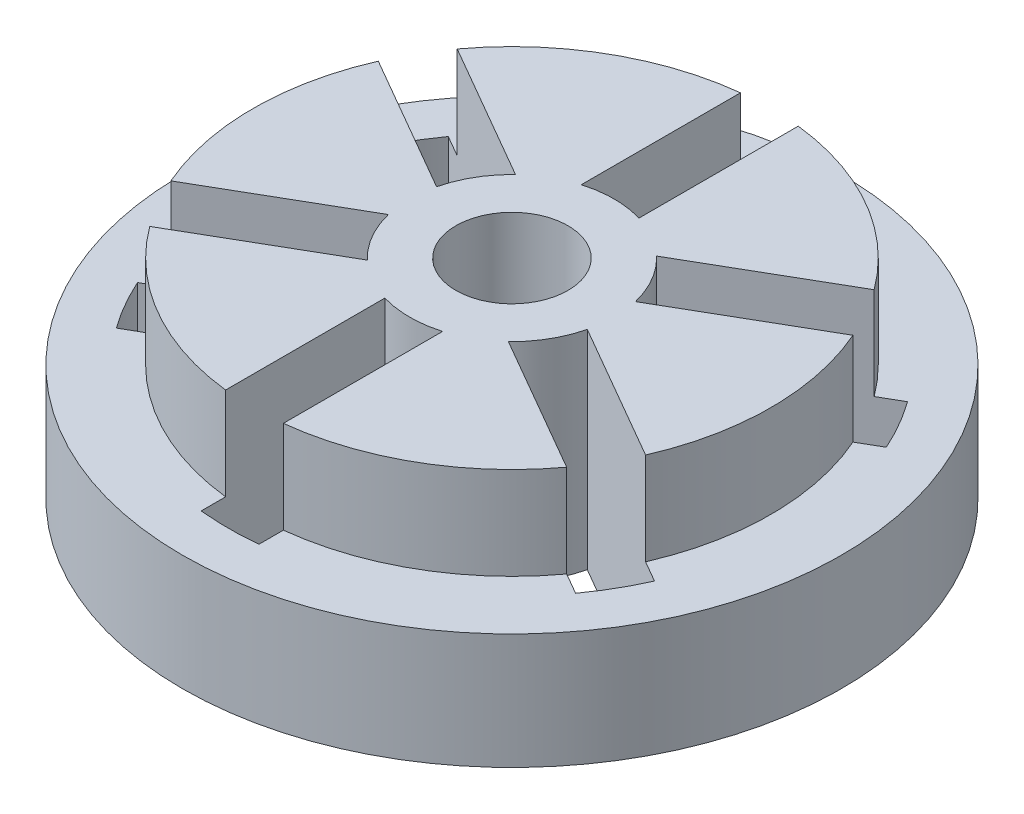
SolidWorks part; units mm, degrees
ref_plane "Front Plane" through (0, 0, 0) normal (0, 0, 1) x (1, 0, 0)
ref_plane "Top Plane" through (0, 0, 0) normal (0, 1, 0) x (1, 0, 0)
ref_plane "Right Plane" through (0, 0, 0) normal (1, 0, 0) x (0, 0, -1)
sketch "Sketch1" plane through (0, 0, 0) normal (0, 1, 0) x (1, 0, 0)
  circle A0 centre (0, 0) radius 28.5
  dimension "D1" = 57
extrude "Boss-Extrude1" add sketch "Sketch1" along normal blind 10
sketch "Sketch2" plane through (0, 10, 0) normal (0, 1, 0) x (1, 0, 0)
  circle A0 centre (0, 0) radius 22.4
  dimension "D1" = 44.8
extrude "Boss-Extrude2" add sketch "Sketch2" along normal blind 8 contours A0
sketch "Sketch3" plane through (0, 18, 0) normal (0, 1, 0) x (1, 0, 0)
  circle A0 centre (0, 0) radius 4.85
  dimension "D1" = 9.7
extrude "Cut-Extrude1" cut sketch "Sketch3" against normal through all
sketch "Sketch6" plane through (0, 0, 0) normal (0, 0, 1) x (1, 0, 0)
  line L0 (0, 0) -> (0, 10)
  line L1 (-28.5, 0) -> (28.5, 0) construction
  line L2 (28.5, 10) -> (-28.5, 10) construction
  circle A0 centre (0, 5) radius 2
  dimension "D1" = 4
sketch "Sketch8" plane through (0, 0, 0) normal (1, 0, 0) x (0, 0, -1)
  line L0 (0, 0) -> (0, 18) construction
  line L1 (4.85, 18) -> (-4.85, 18) construction
sketch "Sketch9" plane through (0, 0, 0) normal (0, -1, 0) x (1, 0, 0)
  line L0 (2, 0) -> (-2, 0) construction
  line L1 (0, 8.85) -> (0, 24.5)
  line L2 (2.4955, 8.4909) -> (2.4955, 24.3726)
  line L3 (-2.5, 8.4896) -> (-2.5, 24.3721)
  circle A0 centre (0, 0) radius 8.85
  circle A1 centre (0, 0) radius 4.85 construction
  circle A4 centre (0, 0) radius 24.5
  circle A5 centre (0, 0) radius 24.5
  dimension "D1" = 4
  dimension "D3" = 2.5
  dimension "D4" = 2.4955
  dimension "D2" = 4
extrude "Cut-Extrude2" cut sketch "Sketch9" against normal through all contours L2 A5 L1 A0 | L1 A5 L3 A0
pattern_circular "CirPattern1" count 6 over 360 about axis through (0, 0, 0) along (0, 1, 0) of "Cut-Extrude2"
